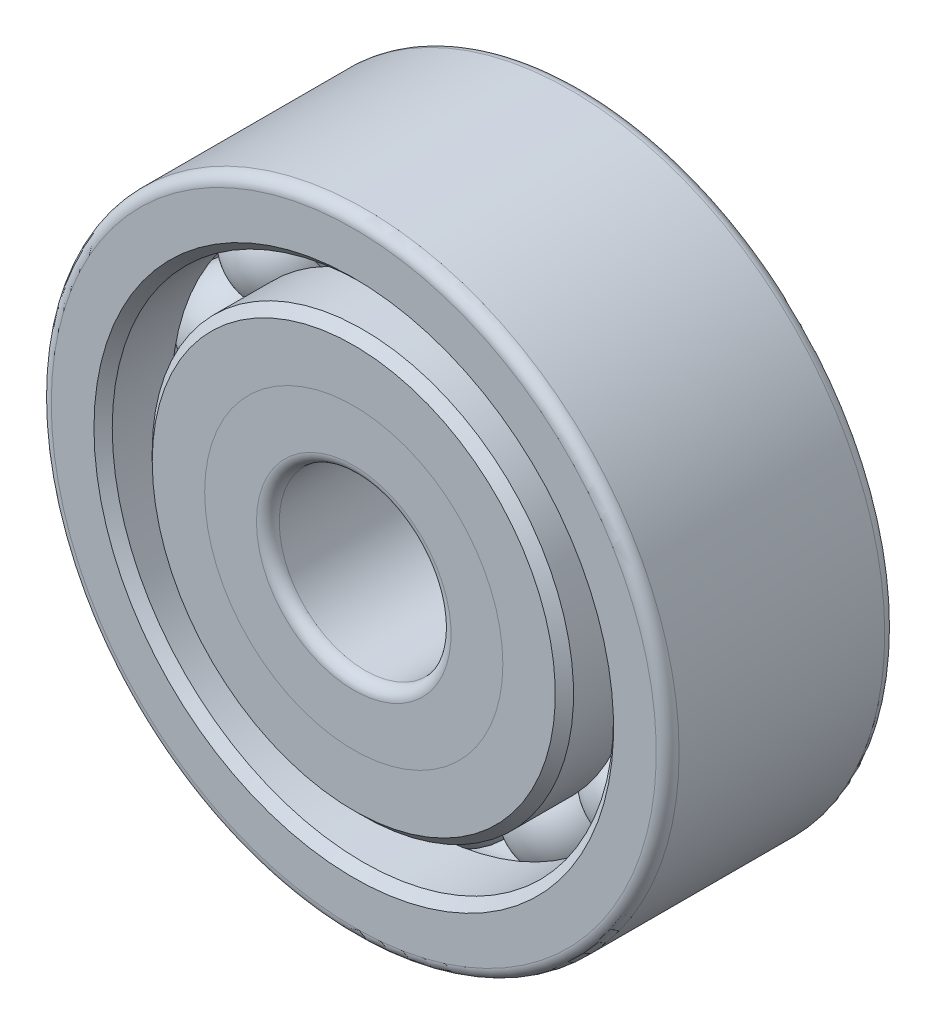
SolidWorks part; units mm, degrees
ref_plane "Front Plane" through (0, 0, 0) normal (0, 0, 1) x (1, 0, 0)
ref_plane "Top Plane" through (0, 0, 0) normal (0, 1, 0) x (1, 0, 0)
ref_plane "Right Plane" through (0, 0, 0) normal (1, 0, 0) x (0, 0, -1)
sketch "Sketch1" plane through (0, 0, 0) normal (1, 0, 0) x (0, 0, -1)
  line L0 (-3.175, 0) -> (3.175, 0) construction
  line L9 (0, 8.7249) -> (0, 0) construction
  line L10 (-3.175, 2.3876) -> (3.175, 2.3876)
  line L11 (3.175, 2.3876) -> (3.175, 5.8552)
  line L12 (3.175, 5.8552) -> (-3.175, 5.8552)
  line L13 (-3.175, 5.8552) -> (-3.175, 2.3876)
  line L14 (-3.175, 6.9667) -> (3.175, 6.9667)
  line L15 (3.175, 6.9667) -> (3.175, 8.7249)
  line L16 (3.175, 8.7249) -> (-3.175, 8.7249)
  line L17 (-3.175, 8.7249) -> (-3.175, 6.9667)
  line L18 (-1.3894, 6.411) -> (1.3894, 6.411) construction
  line L20 (3.175, 4.1436) -> (-3.175, 4.1436) construction
  line L21 (0, 5.0216) -> (0, 4.1436)
  line L22 (0, 4.1436) -> (0, 3.2656)
  line L23 (0, 3.2656) -> (0, 2.3876)
  circle A0 centre (0, 6.411) radius 1.3894
  point P17 (0, 7.8003)
  dimension "ID" = 4.7752
  dimension "OD" = 17.4498
  dimension "Ball Diameter" = 2.7788
  dimension "Ball Pattern Diameter" = 12.8219
  dimension "D6" = 1.1115
  dimension "Width" = 6.35
sketch "Sketch2" plane through (0, 0, 0) normal (0, 0, 1) x (1, 0, 0)
  circle A0 centre (0, 0) radius 6.411 construction
  circle A1 centre (0, 6.411) radius 1.3894
  circle A2 centre (2.7816, 5.7761) radius 1.3894
  circle A3 centre (5.0123, 3.9972) radius 1.3894
  circle A4 centre (6.2502, 1.4266) radius 1.3894
  circle A5 centre (6.2502, -1.4266) radius 1.3894
  circle A6 centre (5.0123, -3.9972) radius 1.3894
  circle A7 centre (2.7816, -5.7761) radius 1.3894
  circle A8 centre (0, -6.411) radius 1.3894
  circle A9 centre (-2.7816, -5.7761) radius 1.3894
  circle A10 centre (-5.0123, -3.9972) radius 1.3894
  circle A11 centre (-6.2502, -1.4266) radius 1.3894
  circle A12 centre (-6.2502, 1.4266) radius 1.3894
  circle A13 centre (-5.0123, 3.9972) radius 1.3894
  circle A15 centre (0, 0) radius 2.3876 construction
  circle A16 centre (0, 0) radius 8.7249 construction
  circle A17 centre (-2.7816, 5.7761) radius 1.3894
  point P36 (0, 0)
  dimension "ID" = 4.7752
  dimension "OD" = 17.4498
  dimension "No. of Balls" = 14
sketch "Sketch3" plane through (0, 0, 0) normal (1, 0, 0) x (0, 0, -1)
  line L1 (3.175, 2.3876) -> (3.175, 5.8552) construction
  line L2 (-3.175, 5.8552) -> (-3.175, 2.3876) construction
  line L3 (3.175, 5.8552) -> (-3.175, 5.8552) construction
  line L5 (3.175, 2.3876) -> (3.175, 5.8552)
  line L6 (-3.175, 5.8552) -> (-3.175, 2.3876)
  line L7 (3.175, 5.8552) -> (-3.175, 5.8552)
  line L8 (-3.175, 8.7249) -> (-3.175, 6.9667) construction
  line L9 (3.175, 8.7249) -> (-3.175, 8.7249) construction
  line L10 (3.175, 6.9667) -> (3.175, 8.7249) construction
  line L11 (-3.175, 6.9667) -> (3.175, 6.9667) construction
  line L12 (-3.175, 8.7249) -> (-3.175, 6.9667)
  line L13 (3.175, 8.7249) -> (-3.175, 8.7249)
  line L14 (3.175, 6.9667) -> (3.175, 8.7249)
  line L15 (-3.175, 6.9667) -> (3.175, 6.9667)
  line L16 (-3.175, 2.3876) -> (3.175, 2.3876) construction
  line L17 (-3.175, 2.3876) -> (3.175, 2.3876)
revolve "Revolve2" add sketch "Sketch3" angle 360 about L0
sketch "Sketch4" plane through (0, 0, 0) normal (1, 0, 0) x (0, 0, -1)
  circle A0 centre (0, 6.411) radius 1.3894 construction
  circle A1 centre (0, 6.411) radius 1.3894
revolve "Cut-Revolve1" cut sketch "Sketch4" angle 360 about L0
sketch "Sketch5" plane through (0, 0, 0) normal (1, 0, 0) x (0, 0, -1)
  line L0 (-1.3894, 6.411) -> (1.3894, 6.411) construction
  line L1 (-1.3894, 6.411) -> (1.3894, 6.411)
  circle A0 centre (0, 6.411) radius 1.3894 construction
  arc A1 (1.3894, 6.411) -> (-1.3894, 6.411) centre (0, 6.411) ccw
revolve "Revolve3" add sketch "Sketch5" angle 360 about L18
pattern_circular "CirPattern1" count 14 over 360 about axis through (0, 0, 0) along (0, 0, 1) of bodies 109
fillet "Fillet1" radius 0.3175 2 edges at (8.7249, 0, 3.175) (8.7249, 0, -3.175)
fillet "Fillet2" radius 0.3175 2 edges at (2.3876, 0, -3.175) (2.3876, 0, 3.175)
chamfer "Chamfer1" distance 0.254 angle 45 2 edges at (6.9667, 0, -3.175) (6.9667, 0, 3.175)
chamfer "Chamfer2" distance 0.254 angle 45 2 edges at (5.8552, 0, 3.175) (5.8552, 0, -3.175)
sketch "Split Line" plane through (0, 0, 0) normal (0, 0, 1) x (1, 0, 0)
  circle A0 centre (0, 0) radius 4.1436
split "Split1" trim tools "Split Line" bodies to split 108 resulting bodies 128 129
equation "\"D1@CirPattern1\"=\"No. of Balls@Sketch2\""
equation "\"D6@Sketch1\"=\"Ball Diameter@Sketch1\"*0.4"
equation "\"D1@Fillet1\"=\"Width@Sketch1\"/20"
equation "\"D1@Fillet2\"=\"Width@Sketch1\"/20"
equation "\"D1@Chamfer1\"=\"Width@Sketch1\"/25"
equation "\"D1@Chamfer2\"=\"Width@Sketch1\"/25"
equation "\"ID@Sketch2\"=\"ID@Sketch1\""
equation "\"OD@Sketch2\" = \"OD@Sketch1\""
